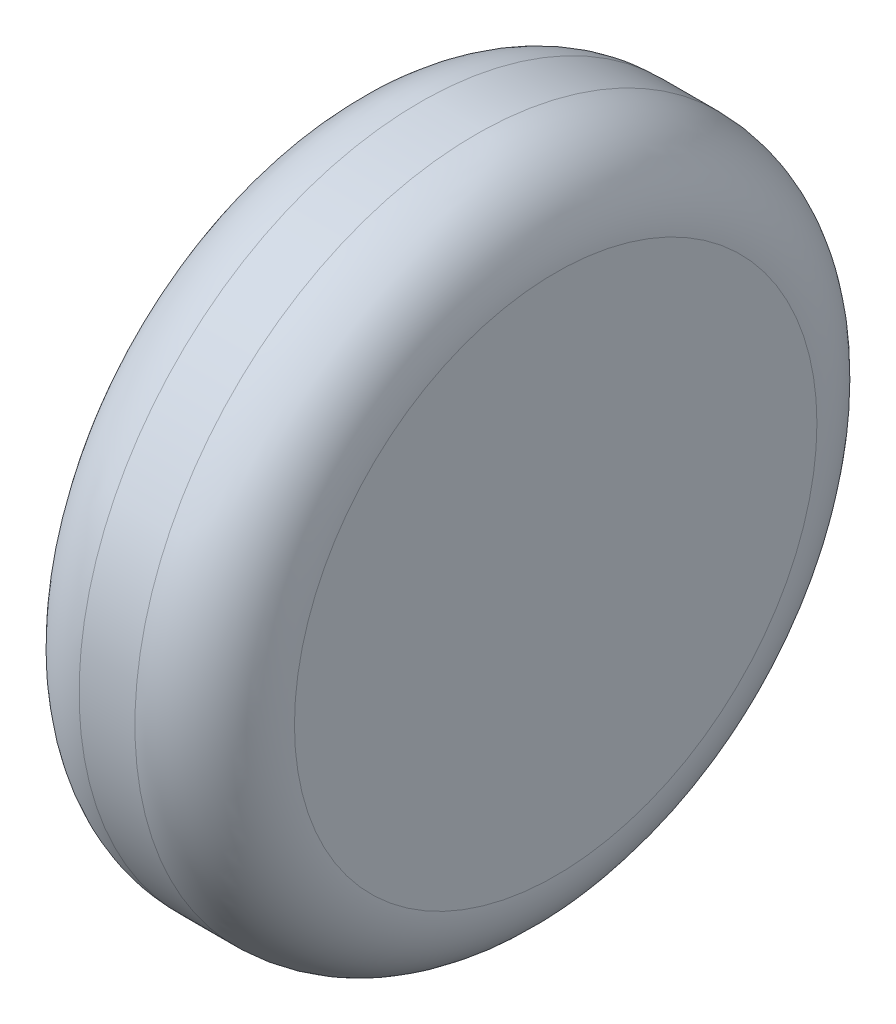
SolidWorks part; units mm, degrees
material "Rubber"
ref_plane "Front Plane" through (0, 0, 0) normal (0, 0, 1) x (1, 0, 0)
ref_plane "Top Plane" through (0, 0, 0) normal (0, 1, 0) x (1, 0, 0)
ref_plane "Right Plane" through (0, 0, 0) normal (1, 0, 0) x (0, 0, -1)
sketch "Sketch1" plane through (0, 0, 0) normal (1, 0, 0) x (0, 0, -1)
  circle A0 centre (0, 0) radius 38
  dimension "D1" = 76
extrude "Boss-Extrude1" add sketch "Sketch1" along normal blind 24
fillet "Fillet1" radius 8.89 2 edges at (0, 0, -38) (24, 0, -38)
sketch "Sketch4" plane through (0, 0, 0) normal (-1, 0, 0) x (0, 0, 1)
  circle A0 centre (0, 0) radius 10.922
  dimension "D1" = 21.844
extrude "Boss-Extrude2" add sketch "Sketch4" along normal blind 3.302
sketch "Sketch5" plane through (-3.302, 0, 0) normal (-1, 0, 0) x (0, 0, 1)
  line L1 (-1.6583, 2.5) -> (1.6583, 2.5)
  arc A0 (-1.6583, 2.5) -> (1.6583, 2.5) centre (0, 0) ccw
  dimension "D1" = 6
extrude "Cut-Extrude3" cut sketch "Sketch5" against normal blind 17.526
